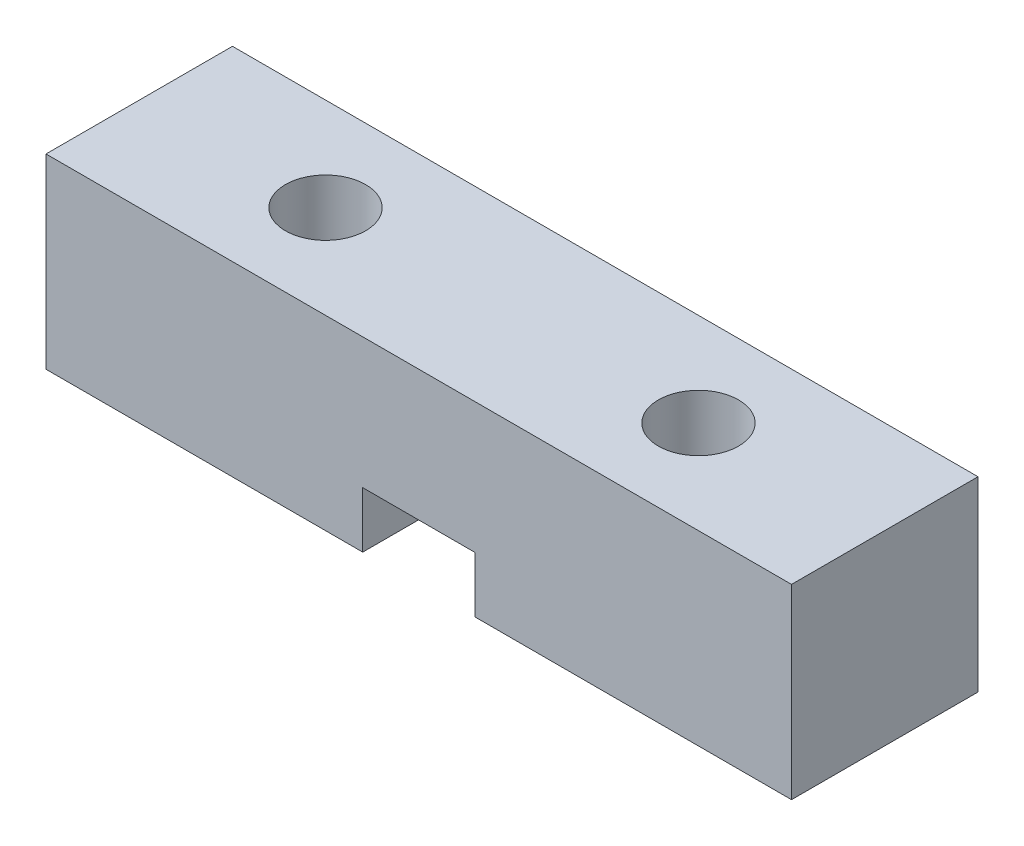
SolidWorks part; units mm, degrees
other "Markup1"
sketch "Sketch4" plane through (54.99, 29.865, 0) normal (0.2832, 0.3918, 0.8754) x (0.9341, 0.0944, -0.3444)
material "6061-T6 (SS)"
ref_plane "Front Plane" through (0, 0, 0) normal (0, 0, 1) x (1, 0, 0)
ref_plane "Top Plane" through (0, 0, 0) normal (0, 1, 0) x (1, 0, 0)
ref_plane "Right Plane" through (0, 0, 0) normal (1, 0, 0) x (0, 0, -1)
sketch "Sketch1" plane through (0, 0, 0) normal (0, 0, 1) x (1, 0, 0)
  line L0 (-65, 30) -> (-65, 10) construction
  line L1 (-74.5, 40) -> (74.5, 40)
  line L2 (-74.5, 40) -> (-74.5, 0)
  line L3 (-74.5, 0) -> (74.5, 0)
  line L4 (74.5, 40) -> (74.5, 0)
  line L5 (31.995, 22.86) -> (38.005, 22.86)
  line L6 (31.995, 22.86) -> (31.995, 16.85)
  line L7 (31.995, 16.85) -> (38.005, 16.85)
  line L8 (38.005, 22.86) -> (38.005, 16.85)
  line L9 (32, 22.855) -> (38, 22.855) construction
  line L10 (32, 22.855) -> (32, 16.855) construction
  line L11 (32, 16.855) -> (38, 16.855) construction
  line L12 (38, 22.855) -> (38, 16.855) construction
  line L13 (0, 0) -> (0, 40) construction
  line L14 (38.005, 19.855) -> (55, 19.855) construction
  line L15 (31.995, 19.855) -> (15, 19.855) construction
  line L16 (15, 19.855) -> (15, 40) construction
  line L17 (55, 19.855) -> (55, 40) construction
  line L18 (31.995, 19.865) -> (15.01, 19.865)
  line L19 (15.01, 19.865) -> (15.01, 40)
  line L20 (38.005, 19.865) -> (54.99, 19.865)
  line L21 (54.99, 19.865) -> (54.99, 40)
  line L22 (15.01, 29.865) -> (54.99, 29.865)
  circle A0 centre (-65, 30) radius 2.5 construction
  circle A1 centre (-65, 10) radius 2.5 construction
  circle A2 centre (65, 10) radius 2.5 construction
  circle A3 centre (65, 30) radius 2.5 construction
  point P10 (0, 0)
  point P14 (35, 22.855)
  point P15 (35, 22.86)
  point P16 (32, 19.855)
  point P17 (31.995, 19.855)
  point P34 (38.005, 19.855)
  dimension "D8" = 5
  dimension "D1" = 6.01
  dimension "D2" = 149
  dimension "D3" = 40
  dimension "D4" = 16.85
  dimension "D5" = 32
  dimension "D6" = 6
  dimension "D7" = 20
  dimension "D9" = 10
  dimension "D10" = 65
  dimension "D11" = 40
  dimension "D14" = 10
  dimension "D12" = 0.01
  dimension "D13" = 0.01
extrude "Boss-Extrude1" add sketch "Sketch1" against normal blind 10 contours L20 L21 L1 L19 L18 L6 L5 L8
sketch "Sketch2" plane through (0, 19.865, 0) normal (0, -1, 0) x (1, 0, 0)
  line L0 (54.99, 0) -> (38.005, 0) construction
  line L1 (38.005, 0) -> (38.005, -10) construction
  line L2 (38.005, -10) -> (54.99, -10) construction
  line L3 (54.99, -10) -> (54.99, 0) construction
  line L4 (31.995, 0) -> (15.01, 0) construction
  line L5 (15.01, 0) -> (15.01, -10) construction
  line L6 (15.01, -10) -> (31.995, -10) construction
  line L7 (31.995, -10) -> (31.995, 0) construction
  line L8 (54.99, 0) -> (38.005, 0)
  line L9 (38.005, 0) -> (38.005, -10)
  line L10 (38.005, -10) -> (54.99, -10)
  line L11 (54.99, -10) -> (54.99, 0)
  line L12 (31.995, 0) -> (15.01, 0)
  line L13 (15.01, 0) -> (15.01, -10)
  line L14 (15.01, -10) -> (31.995, -10)
  line L15 (31.995, -10) -> (31.995, 0)
  line L16 (25, -5) -> (45, -5)
  line L17 (31.995, 0) -> (38.005, 0)
  circle A0 centre (25, -5) radius 2 construction
  circle A1 centre (45, -5) radius 2 construction
  point P10 (15.01, -5)
  point P12 (35, 0)
  point P14 (35, -5)
  dimension "D2" = 4
  dimension "D4" = 9.99
  dimension "D1" = 20
  dimension "D3" = 9.99
hole_wizard "M4 Clearance Hole1" positions "3DSketch1" profile "Sketch3" hole size "M4" standard "ANSI Metric" end condition up to next
sketch3d "3DSketch1"
  point P0 (25, 19.865, -5)
  point P2 (45, 19.865, -5)
sketch "Sketch3" plane through (25, 19.865, -5) normal (1, 0, 0) x (0, 0, -1)
  line L0 (0, 0) -> (0, 10)
  line L1 (0, 10) -> (2.15, 10)
  line L2 (2.15, 10) -> (2.15, 0)
  line L5 (2.15, 0) -> (0, 0)
  line L11 (0, -6.35) -> (0, 107.95) construction
  dimension "Thru Hole Dia." = 4.3
  dimension "Thru Hole Depth" = 10
